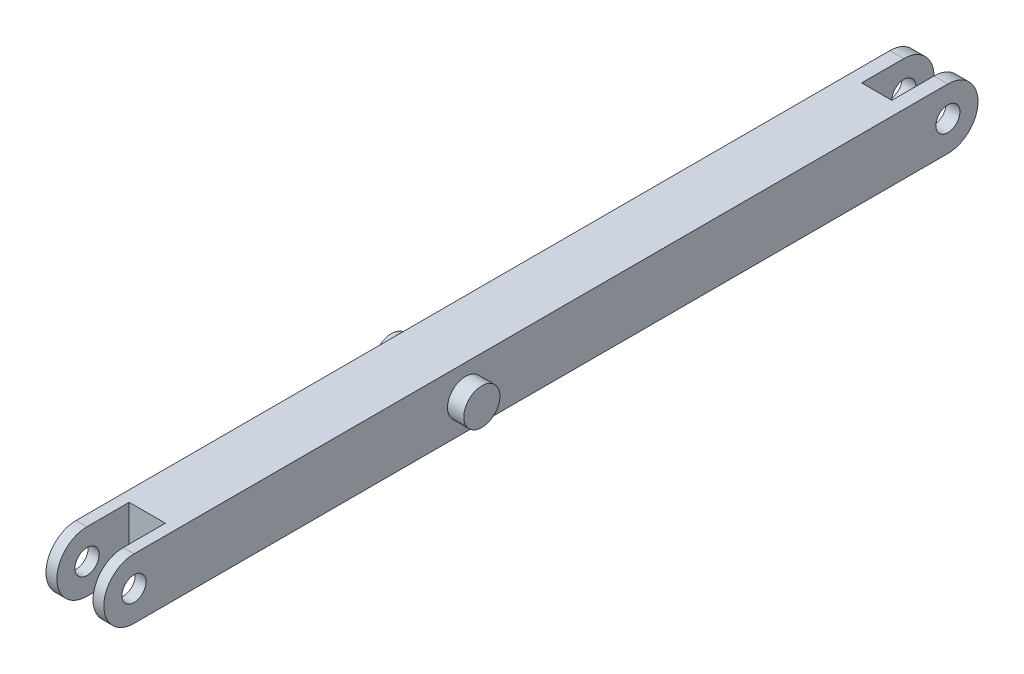
SolidWorks part; units mm, degrees
material "1060 Alloy"
ref_plane "Front Plane" through (0, 0, 0) normal (0, 0, 1) x (1, 0, 0)
ref_plane "Top Plane" through (0, 0, 0) normal (0, 1, 0) x (1, 0, 0)
ref_plane "Right Plane" through (0, 0, 0) normal (1, 0, 0) x (0, 0, -1)
sketch "Sketch1" plane through (0, 0, 0) normal (1, 0, 0) x (0, 0, -1)
  line L0 (-300, 0) -> (0, 0) construction
  line L1 (-275, 25) -> (400, 25)
  line L3 (-275, -25) -> (400, -25)
  line L5 (0, 0) -> (400, 0) construction
  circle A0 centre (-275, 0) radius 10
  arc A1 (-275, 25) -> (-275, -25) centre (-275, 0) ccw
  arc A2 (400, -25) -> (400, 25) centre (400, 0) ccw
  circle A3 centre (400, 0) radius 10
  dimension "D3" = 275
  dimension "D6" = 20
  dimension "D1" = 50
  dimension "D5" = 400
extrude "Boss-Extrude1" add sketch "Sketch1" along normal mid plane 48
sketch "Sketch2" plane through (0, 25, 0) normal (0, 1, 0) x (1, 0, 0)
  line L0 (24, 425) -> (-24, 425) construction
  line L1 (-12.5, 425) -> (12.5, 425)
  line L2 (-12.5, 425) -> (-12.5, 365)
  line L3 (-12.5, 365) -> (12.5, 365)
  line L4 (12.5, 425) -> (12.5, 365)
  line L5 (0, 0) -> (0, 365) construction
  line L6 (-24, -300) -> (24, -300) construction
  line L7 (-15, -300) -> (15, -300)
  line L8 (-15, -300) -> (-15, -240)
  line L9 (-15, -240) -> (15, -240)
  line L10 (15, -300) -> (15, -240)
  line L11 (0, -240) -> (0, 0) construction
  dimension "D1" = 25
  dimension "D2" = 60
  dimension "D3" = 30
  dimension "D4" = 60
extrude "Cut-Extrude1" cut sketch "Sketch2" against normal through all
sketch "Sketch3" plane through (0, 0, 0) normal (1, 0, 0) x (0, 0, -1)
  circle A0 centre (0, 0) radius 15
  dimension "D1" = 30
extrude "Boss-Extrude2" add sketch "Sketch3" along normal mid plane 75
equation "\"A\"= 100"
equation "\"B\"= 100mm"
equation "\"C\"= 100"
equation "\"D\"= 100"
equation "\"E\"= 100"
